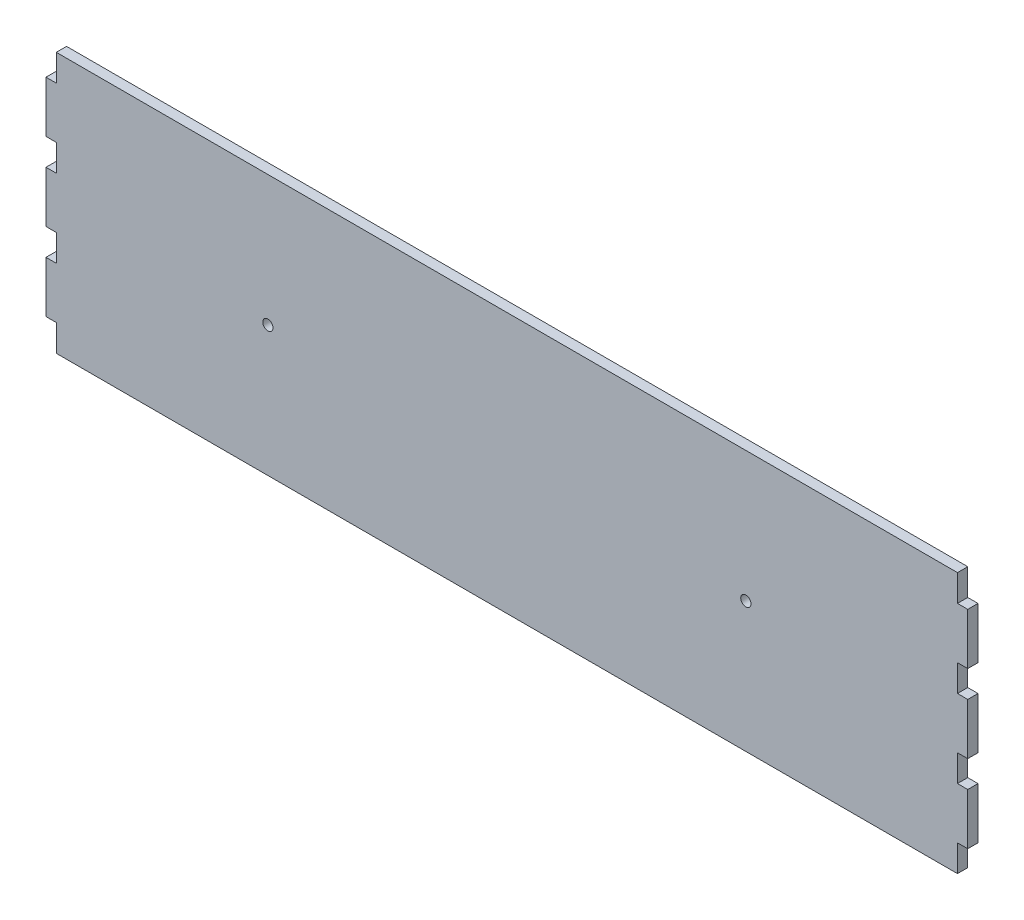
SolidWorks part; units mm, degrees
material "ENPH 253 Hardboard"
ref_plane "Front Plane" through (0, 0, 0) normal (0, 0, 1) x (1, 0, 0)
ref_plane "Top Plane" through (0, 0, 0) normal (0, 1, 0) x (1, 0, 0)
ref_plane "Right Plane" through (0, 0, 0) normal (1, 0, 0) x (0, 0, -1)
sketch "Sketch1" plane through (0, 0, 0) normal (0, 0, 1) x (1, 0, 0)
  line L1 (-134.7, 38.1) -> (134.7, 38.1)
  line L2 (-134.7, 38.1) -> (-134.7, -38.1)
  line L3 (-134.7, -38.1) -> (134.7, -38.1)
  line L4 (134.7, 38.1) -> (134.7, -38.1)
  line L5 (-134.7, 38.1) -> (134.7, -38.1) construction
  line L6 (-134.7, -38.1) -> (134.7, 38.1) construction
  point P0 (0, 0)
  dimension "D1" = 269.4
  dimension "D2" = 76.2
extrude "Boss-Extrude1" add sketch "Sketch1" along normal blind 3
sketch "Sketch2" plane through (0, 0, 3) normal (0, 0, 1) x (1, 0, 0)
  line L1 (-134.7, 38.1) -> (-131.7, 38.1)
  line L2 (-134.7, 38.1) -> (-134.7, 30.3)
  line L3 (-134.7, 30.3) -> (-131.7, 30.3)
  line L4 (-131.7, 38.1) -> (-131.7, 30.3)
  dimension "D1" = 3
  dimension "D2" = 7.8
extrude "Cut-Extrude1" cut sketch "Sketch2" against normal through all
pattern_linear "LPattern1" count 4 spacing 22.8 along (0, -1, 0) of "Cut-Extrude1"
mirror "Mirror1" about plane through (0, 0, 0) normal (1, 0, 0) of "LPattern1", "Cut-Extrude1"
hole_wizard "Ø3.0mm Clearance Dowel Hole1" positions "Sketch3" profile "Sketch4" hole size "Ø3.0" standard "ANSI Metric" end condition through all
sketch "Sketch3" plane through (0, 0, 3) normal (0, 0, 1) x (1, 0, 0)
  line L0 (-134.7, 7.5) -> (-134.7, -7.5) construction
  line L1 (134.7, -7.5) -> (134.7, 7.5) construction
  point P0 (-69.85, 0)
  point P2 (69.85, 0)
  dimension "D1" = 64.85
  dimension "D2" = 64.85
sketch "Sketch4" plane through (-69.85, 0, 3) normal (1, 0, 0) x (0, -1, 0)
  line L0 (0, 0) -> (0, 3)
  line L1 (0, 3) -> (1.5, 3)
  line L2 (1.5, 3) -> (1.5, 0)
  line L5 (1.5, 0) -> (0, 0)
  line L11 (0, -6.35) -> (0, 107.95) construction
  dimension "Thru Hole Dia." = 3
  dimension "Thru Hole Depth" = 3
equation "\"D2@Sketch3\"=\"D1@Sketch3\""
